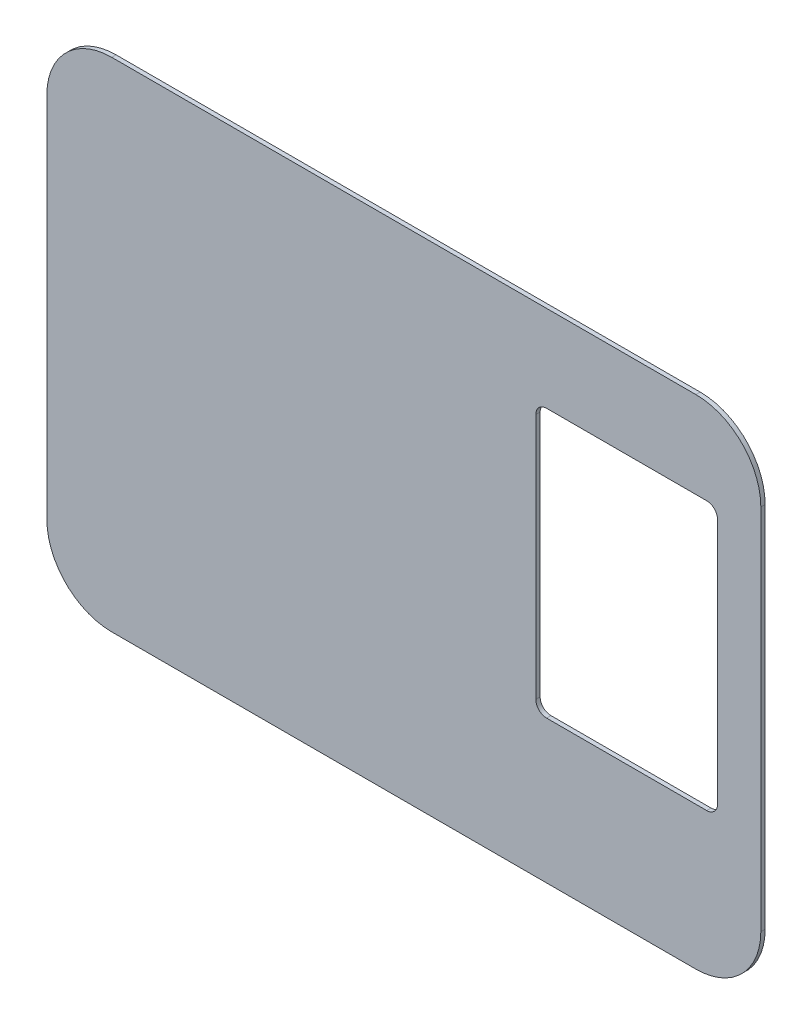
SolidWorks part; units mm, degrees
ref_plane "Front Plane" through (0, 0, 0) normal (0, 0, 1) x (1, 0, 0)
ref_plane "Top Plane" through (0, 0, 0) normal (0, 1, 0) x (1, 0, 0)
ref_plane "Right Plane" through (0, 0, 0) normal (1, 0, 0) x (0, 0, -1)
sketch "Sketch1" plane through (0, 0, 0) normal (0, 0, 1) x (1, 0, 0)
  line L1 (-165, 115) -> (165, 115)
  line L2 (-165, 115) -> (-165, -115)
  line L3 (-165, -115) -> (165, -115)
  line L4 (165, 115) -> (165, -115)
  line L5 (-165, 115) -> (165, -115) construction
  line L6 (-165, -115) -> (165, 115) construction
  point P0 (0, 0)
  dimension "D1" = 230
  dimension "D2" = 330
extrude "Boss-Extrude1" add sketch "Sketch1" along normal blind 2
sketch "Sketch2" plane through (0, 0, 0) normal (0, 0, -1) x (-1, 0, 0)
  line L0 (31.1795, 6.2282) -> (31.1795, -73.7718) construction
  line L1 (-140, 75) -> (-66, 75)
  line L2 (-145, 70) -> (-145, -44)
  line L3 (-140, -49) -> (-66, -49)
  line L4 (-61, 70) -> (-61, -44)
  line L5 (31.1795, 6.2282) -> (31.1795, -73.7718)
  line L6 (-165, -115) -> (-165, 115) construction
  line L7 (-165, -115) -> (-165, 115)
  line L8 (-165, 115) -> (165, 115) construction
  arc A0 (-145, -44) -> (-140, -49) centre (-140, -44) ccw
  arc A1 (-66, -49) -> (-61, -44) centre (-66, -44) ccw
  arc A2 (-66, 75) -> (-61, 70) centre (-66, 70) cw
  arc A3 (-140, 75) -> (-145, 70) centre (-140, 70) ccw
  point P6 (0, 0)
  point P7 (0, 0)
  point P16 (-145, -49)
  point P19 (-61, -49)
  point P24 (-145, 75)
  dimension "D5" = 5
  dimension "D1" = 84
  dimension "D2" = 124
  dimension "D3" = 20
  dimension "D4" = 40
extrude "Cut-Extrude1" cut sketch "Sketch2" against normal up to surface (2 mm away) contours L1 A3 L2 A0 L3 A1 L4 A2 up to face at (0, 0, 2)
fillet "Fillet1" radius 30 4 edges at (-165, -115, 1) (165, -115, 1) (165, 115, 1) (-165, 115, 1)
